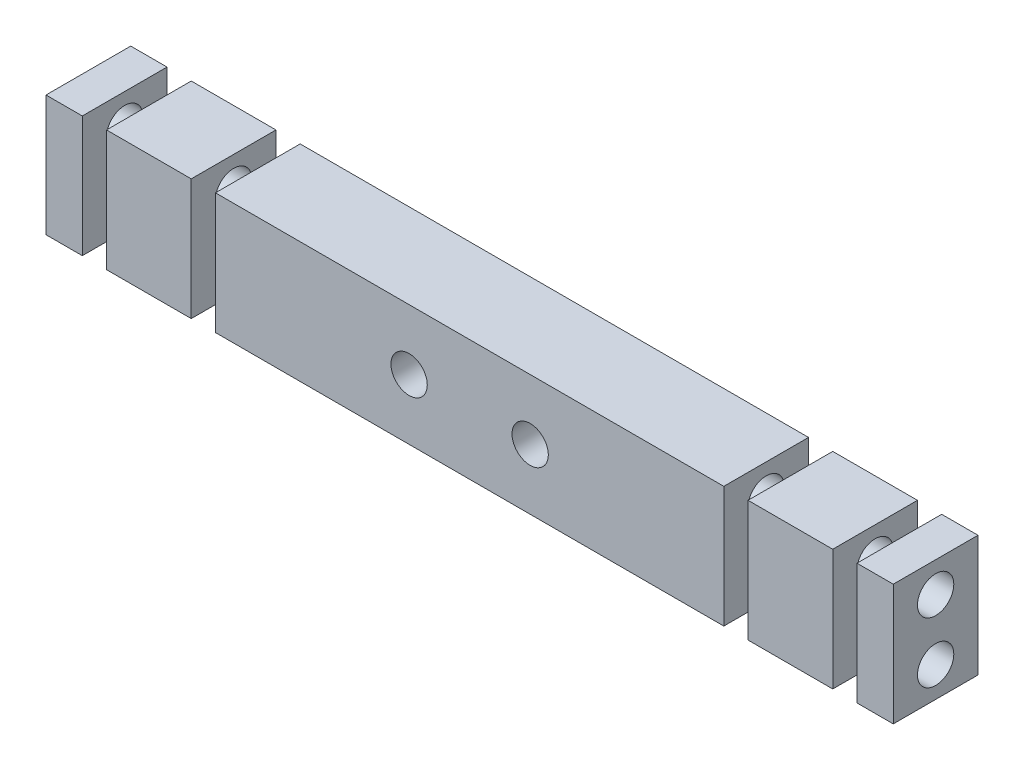
SolidWorks part; units mm, degrees
ref_plane "Спереди" through (0, 0, 0) normal (0, 0, 1) x (1, 0, 0)
ref_plane "Сверху" through (0, 0, 0) normal (0, 1, 0) x (1, 0, 0)
ref_plane "Справа" through (0, 0, 0) normal (1, 0, 0) x (0, 0, -1)
sketch "Эскиз1" plane through (0, 0, 0) normal (0, 1, 0) x (1, 0, 0)
  line L1 (-52.4324, 5.5484) -> (17.5676, 5.5484)
  line L2 (-52.4324, 5.5484) -> (-52.4324, -1.4516)
  line L3 (-52.4324, -1.4516) -> (17.5676, -1.4516)
  line L4 (17.5676, 5.5484) -> (17.5676, -1.4516)
  dimension "D1" = 70
  dimension "D2" = 7
extrude "Бобышка-Вытянуть1" add sketch "Эскиз1" along normal blind 10
sketch "Эскиз2" plane through (0, 0, -5.5484) normal (0, 0, -1) x (-1, 0, 0)
  line L0 (17.4324, 10) -> (17.4324, -4.9951) construction
  line L1 (-17.5676, 10) -> (52.4324, 10) construction
  line L2 (-14.5676, 10) -> (-14.5676, 0)
  line L3 (-17.5676, 0) -> (52.4324, 0) construction
  line L4 (-12.5676, 10) -> (-12.5676, 0)
  line L5 (49.4324, 10) -> (49.4324, 0)
  line L6 (47.4324, 10) -> (47.4324, 0)
  line L7 (40.4324, 10) -> (40.4324, 0)
  line L8 (-5.5676, 10) -> (-5.5676, 0)
  line L9 (38.4324, 10) -> (38.4324, 0)
  line L10 (-3.5676, 0) -> (-3.5676, 10)
  line L11 (-14.5676, 10) -> (-12.5676, 10)
  line L12 (-14.5676, 0) -> (-12.5676, 0)
  line L13 (-5.5676, 10) -> (-3.5676, 10)
  line L14 (-5.5676, 0) -> (-3.5676, 0)
  line L15 (38.4324, 10) -> (40.4324, 10)
  line L16 (47.4324, 10) -> (49.4324, 10)
  line L17 (47.4324, 0) -> (49.4324, 0)
  line L18 (49.4324, 0) -> (49.3828, 0.0338)
  line L19 (38.4324, 0) -> (40.4324, 0)
  dimension "D1" = 35
  dimension "D2" = 3
  dimension "D3" = 2
  dimension "D4" = 3
  dimension "D5" = 2
  dimension "D6" = 7
  dimension "D7" = 7
  dimension "D8" = 2
  dimension "D9" = 2
extrude "Вырез-Вытянуть1" cut sketch "Эскиз2" against normal blind 7
sketch "Эскиз4" plane through (17.5676, 0, 0) normal (1, 0, 0) x (0, 0, -1)
  line L0 (-1.4516, 10) -> (5.5484, 0) construction
  line L1 (5.5484, 10) -> (-1.4516, 0) construction
  line L2 (2.0484, 10) -> (2.0484, 5) construction
  line L3 (-1.4516, 10) -> (5.5484, 10) construction
  line L4 (2.0484, 5) -> (2.0484, 0) construction
  line L5 (-1.4516, 0) -> (5.5484, 0) construction
  circle A0 centre (2.0484, 7.5) radius 1.5
  circle A1 centre (2.0484, 2.5) radius 1.5
extrude "Вырез-Вытянуть2" cut sketch "Эскиз4" against normal blind 20
sketch "Эскиз5" plane through (-52.4324, 0, 0) normal (-1, 0, 0) x (0, 0, 1)
  line L0 (1.4516, 10) -> (-5.5484, 0) construction
  line L1 (-5.5484, 10) -> (1.4516, 0) construction
  line L2 (-2.0484, 10) -> (-2.0484, 5) construction
  line L3 (-5.5484, 10) -> (1.4516, 10) construction
  line L4 (-2.0484, 5) -> (-2.0484, 0) construction
  line L5 (-5.5484, 0) -> (1.4516, 0) construction
  circle A0 centre (-2.0484, 7.5) radius 1.5
  circle A1 centre (-2.0484, 2.5) radius 1.5
extrude "Вырез-Вытянуть3" cut sketch "Эскиз5" against normal blind 20
sketch "Эскиз6" plane through (0, 0, 1.4516) normal (0, 0, 1) x (1, 0, 0)
  line L0 (-38.4324, 10) -> (3.5676, 10) construction
  line L1 (-17.4324, 10) -> (-17.4324, 0) construction
  line L2 (-38.4324, 0) -> (3.5676, 0) construction
  line L3 (-22.4324, 10) -> (-22.4324, 0) construction
  line L4 (-12.4324, 10) -> (-12.4324, 0) construction
  line L5 (-17.4324, 5) -> (-4.8887, 5) construction
  line L6 (-17.4324, 5) -> (-27.4701, 5) construction
  circle A0 centre (-22.4324, 5) radius 1.5
  circle A1 centre (-12.4324, 5) radius 1.5
  dimension "D3" = 5
  dimension "D1" = 5
  dimension "D2" = 5
extrude "Вырез-Вытянуть4" cut sketch "Эскиз6" against normal blind 7
